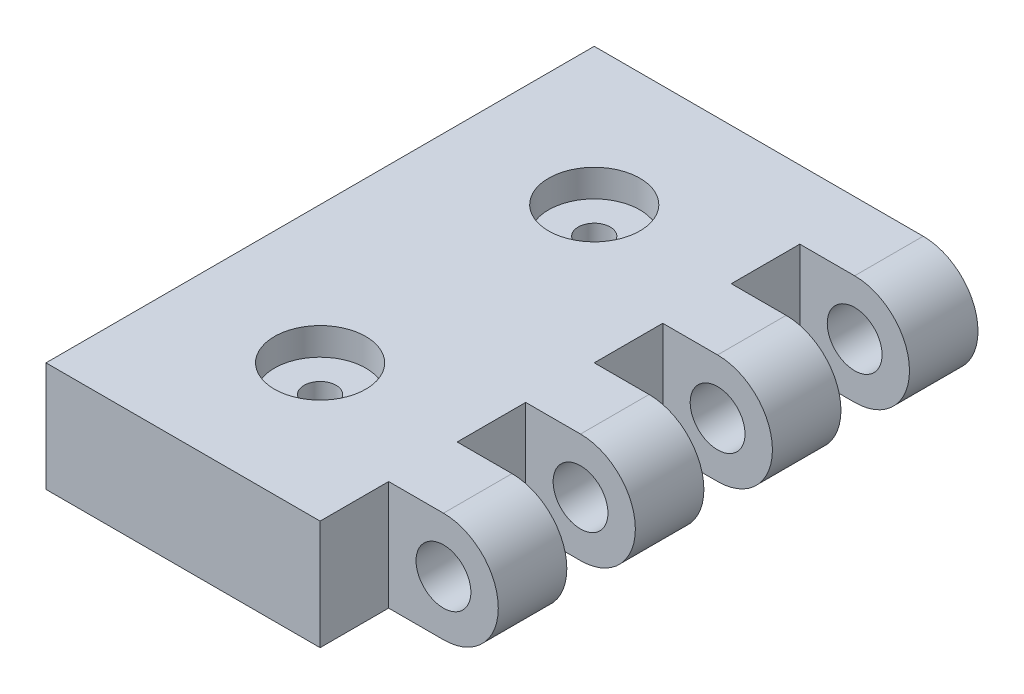
SolidWorks part; units mm, degrees
ref_plane "Front" through (0, 0, 0) normal (0, 0, 1) x (1, 0, 0)
ref_plane "Top" through (0, 0, 0) normal (0, 1, 0) x (1, 0, 0)
ref_plane "Right" through (0, 0, 0) normal (1, 0, 0) x (0, 0, -1)
sketch "Sketch1" plane through (0, 0, 0) normal (0, 1, 0) x (1, 0, 0)
  line L1 (0, 0) -> (-30, 0)
  line L2 (0, 0) -> (0, 60)
  line L3 (0, 60) -> (-30, 60)
  line L4 (-30, 0) -> (-30, 60)
  dimension "D1" = 60
  dimension "D2" = 30
extrude "Boss-Extrude1" add sketch "Sketch1" along normal blind 12
sketch "Sketch2" plane through (0, 0, 0) normal (0, 0, 1) x (1, 0, 0)
  line L0 (0, 0) -> (13.9056, 0) construction
  line L1 (0, 12) -> (0, 0) construction
  line L2 (0, 6) -> (0, 0)
  line L3 (0, 0) -> (6, 0)
  line L4 (0, 6) -> (0, 12)
  line L5 (0, 12) -> (6, 12)
  arc A0 (6, 0) -> (6, 12) centre (6, 6) ccw
  circle A1 centre (6, 6) radius 3
  dimension "D1" = 12
  dimension "D2" = 6
extrude "Boss-Extrude2" add sketch "Sketch2" against normal up to surface (60 mm away) up to face at (-15, 6, -60)
sketch "Sketch3" plane through (0, 12, 0) normal (0, 1, 0) x (1, 0, 0)
  line L1 (0, 52.5) -> (12, 52.5)
  line L2 (0, 52.5) -> (0, 45)
  line L3 (0, 45) -> (12, 45)
  line L4 (12, 52.5) -> (12, 45)
  line L5 (12, 0) -> (12, 60) construction
  line L6 (6, 60) -> (-30, 60) construction
  dimension "D1" = 12
  dimension "D2" = 7.5
  dimension "7.5" = 7.5
extrude "Cut-Extrude1" cut sketch "Sketch3" against normal through all
pattern_linear "LPattern1" count 4 spacing 15 along (0, 0, 1) of "Cut-Extrude1"
sketch "Sketch4" plane through (0, 12, 0) normal (0, 1, 0) x (1, 0, 0)
  line L1 (6, 60) -> (-30, 60) construction
  line L2 (-30, 0) -> (0, 0) construction
  line L3 (-15, 0) -> (-15, 45) construction
  circle A0 centre (-15, 45) radius 1.75
  circle A1 centre (-15, 15) radius 1.75
  dimension "D4" = 3.5
  dimension "D2" = 15
  dimension "D3" = 15
extrude "Cut-Extrude2" cut sketch "Sketch4" against normal through all
sketch "Sketch5" plane through (0, 12, 0) normal (0, 1, 0) x (1, 0, 0)
  circle A0 centre (-15, 45) radius 5
  circle A1 centre (-15, 15) radius 5
  dimension "D1" = 10
extrude "Cut-Extrude3" cut sketch "Sketch5" against normal blind 3
pattern_linear "LPattern2" count 2 spacing 9 along (0, -1, 0) of "Cut-Extrude3"
